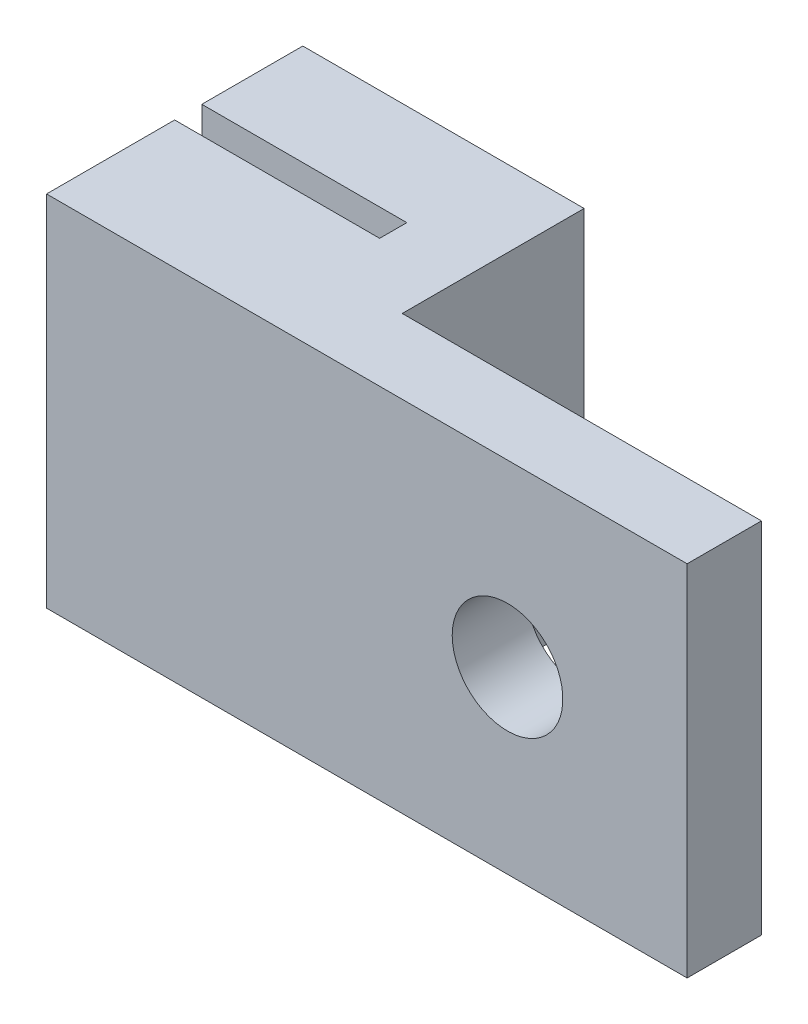
SolidWorks part; units mm, degrees
ref_plane "Front Plane" through (0, 0, 0) normal (0, 0, 1) x (1, 0, 0)
ref_plane "Top Plane" through (0, 0, 0) normal (0, 1, 0) x (1, 0, 0)
ref_plane "Right Plane" through (0, 0, 0) normal (1, 0, 0) x (0, 0, -1)
sketch "Sketch1" plane through (0, 0, 0) normal (0, 1, 0) x (1, 0, 0)
  line L1 (-1237.7101, -397.7364) -> (-1212.7101, -397.7364)
  line L2 (-1237.7101, -397.7364) -> (-1237.7101, -387.7364)
  line L3 (-1237.7101, -387.7364) -> (-1212.7101, -387.7364)
  line L4 (-1212.7101, -397.7364) -> (-1212.7101, -387.7364)
  line L5 (-1237.7101, -391.6764) -> (-1229.7101, -391.6764)
  line L6 (-1237.7101, -391.6764) -> (-1237.7101, -392.7364)
  line L7 (-1237.7101, -392.7364) -> (-1229.7101, -392.7364)
  line L8 (-1229.7101, -391.6764) -> (-1229.7101, -392.7364)
  dimension "D1" = 5
  dimension "D2" = 25
  dimension "D3" = 8
  dimension "D4" = 1.06
  dimension "D5" = 10
extrude "Boss-Extrude1" add sketch "Sketch1" against normal blind 14 contours L5 L8 L7 L2 L1 L4 L3
sketch "Sketch2" plane through (0, 0, 0) normal (0, 1, 0) x (1, 0, 0)
  line L0 (-1237.7101, -387.7364) -> (-1212.7101, -387.7364) construction
  line L1 (-1226.7298, -387.7364) -> (-1212.7101, -387.7364)
  line L2 (-1226.7298, -387.7364) -> (-1226.7298, -394.836)
  line L3 (-1226.7298, -394.836) -> (-1212.7101, -394.836)
  line L4 (-1212.7101, -387.7364) -> (-1212.7101, -394.836)
  line L5 (-1212.7101, -397.7364) -> (-1212.7101, -387.7364) construction
extrude "Cut-Extrude1" cut sketch "Sketch2" against normal through all
sketch "Sketch4" plane through (0, 0, 394.836) normal (0, 0, -1) x (-1, 0, 0)
  line L0 (1226.7298, 0) -> (1212.7101, 0) construction
  line L1 (1219.72, 0) -> (1219.72, -14) construction
  line L2 (1226.7298, -14) -> (1212.7101, -14) construction
  line L3 (1212.7101, -7) -> (1226.7298, -7) construction
  line L4 (1212.7101, -14) -> (1212.7101, 0) construction
  line L5 (1226.7298, -14) -> (1226.7298, 0) construction
  circle A0 centre (1219.72, -7) radius 2.159
  dimension "D1" = 4.318
extrude "Cut-Extrude2" cut sketch "Sketch4" against normal through all
